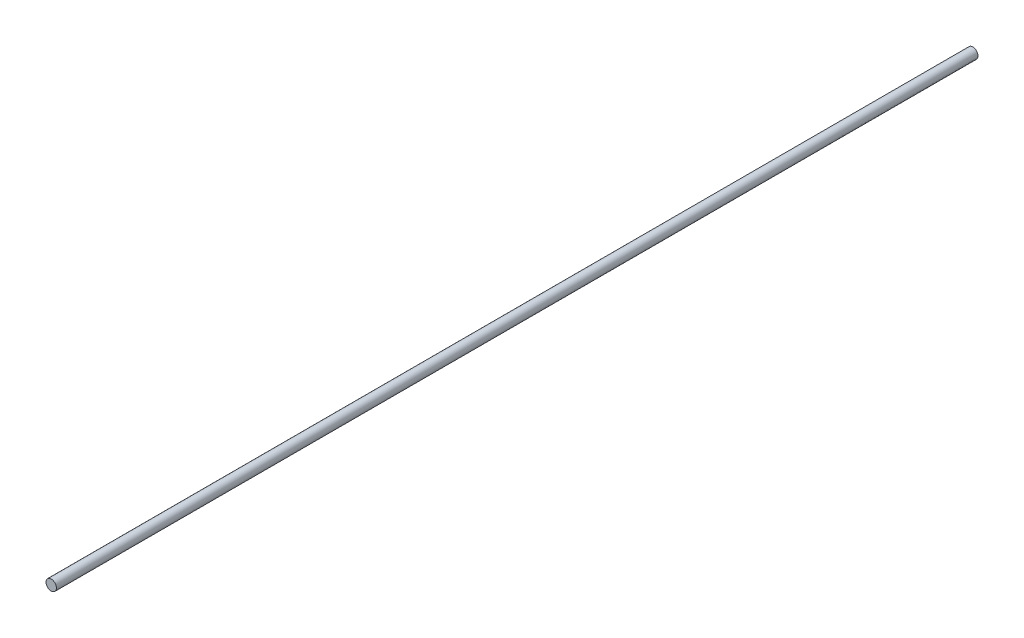
SolidWorks part; units mm, degrees
material "6061-T6 (SS)"
ref_plane "Front Plane" through (0, 0, 0) normal (0, 0, 1) x (1, 0, 0)
ref_plane "Top Plane" through (0, 0, 0) normal (0, 1, 0) x (1, 0, 0)
ref_plane "Right Plane" through (0, 0, 0) normal (1, 0, 0) x (0, 0, -1)
sketch "Sketch1" plane through (0, 0, 0) normal (0, 0, 1) x (1, 0, 0)
  circle A0 centre (0, 0.0451) radius 6.35
  dimension "D1" = 12.7
extrude "Boss-Extrude1" add sketch "Sketch1" along normal blind 1122.172 contours A0
equation "\"F\"= 400'lbf"
equation "\"E\"= 10000000'psi"
equation "\"delta\"= 0.009in'in"
equation "\"D\"= 0.5in'in"
equation "\"A\"= pi * ( \"D\" / 2 ) ^ 2'in^2"
equation "\"L\"= ( \"delta\" * \"A\" * \"E\" ) / \"F\"'in"
